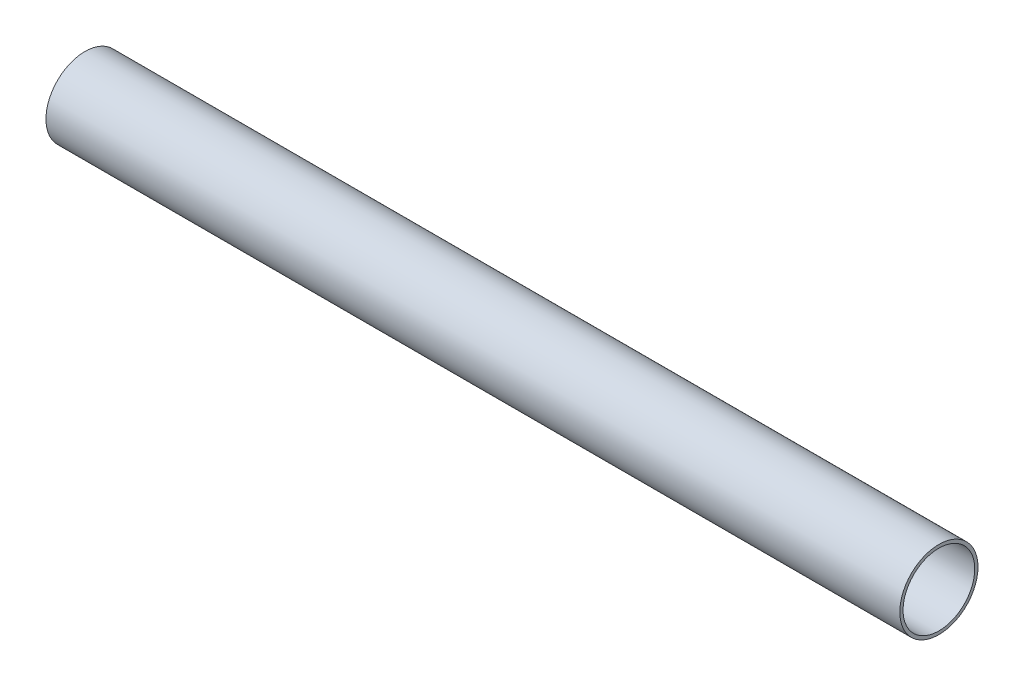
SolidWorks part; units mm, degrees
material "Rubber"
ref_plane "Front Plane" through (0, 0, 0) normal (0, 0, 1) x (1, 0, 0)
ref_plane "Top Plane" through (0, 0, 0) normal (0, 1, 0) x (1, 0, 0)
ref_plane "Right Plane" through (0, 0, 0) normal (1, 0, 0) x (0, 0, -1)
sketch "Sketch1" plane through (0, 0, 0) normal (1, 0, 0) x (0, 0, -1)
  circle A0 centre (0, 0) radius 17.4625
  circle A1 centre (0, 0) radius 19.05
  dimension "D1" = 34.925
  dimension "D2" = 38.1
extrude "Boss-Extrude1" add sketch "Sketch1" along normal blind 415.9758
